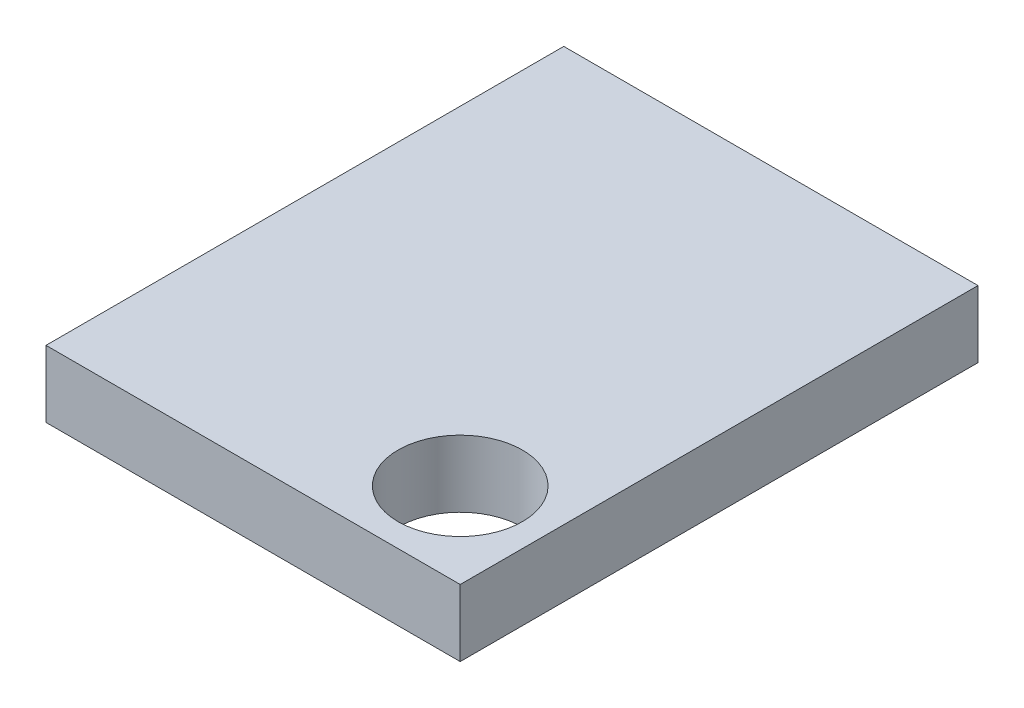
SolidWorks part; units mm, degrees
ref_plane "Front Plane" through (0, 0, 0) normal (0, 0, 1) x (1, 0, 0)
ref_plane "Top Plane" through (0, 0, 0) normal (0, 1, 0) x (1, 0, 0)
ref_plane "Right Plane" through (0, 0, 0) normal (1, 0, 0) x (0, 0, -1)
sketch "Sketch1" plane through (0, 0, 0) normal (0, 1, 0) x (1, 0, 0)
  line L1 (-5.08, -6.35) -> (5.08, -6.35)
  line L2 (-5.08, -6.35) -> (-5.08, 6.35)
  line L3 (-5.08, 6.35) -> (5.08, 6.35)
  line L4 (5.08, -6.35) -> (5.08, 6.35)
  line L5 (-5.08, -6.35) -> (5.08, 6.35) construction
  line L6 (-5.08, 6.35) -> (5.08, -6.35) construction
  point P0 (0, 0)
  dimension "D1" = 12.7
  dimension "D2" = 10.16
extrude "Boss-Extrude1" add sketch "Sketch1" along normal blind 1.6383
sketch "Sketch2" plane through (0, 1.6383, 0) normal (0, 1, 0) x (1, 0, 0)
  line L0 (0, 0) -> (29.1011, 0) construction
  line L1 (5.08, -6.35) -> (5.08, 6.35) construction
  line L2 (-5.08, -6.35) -> (5.08, -6.35) construction
  circle A0 centre (2.9845, -4.2545) radius 1.524
  dimension "D1" = 3.048
  dimension "D3" = 2.0955
  dimension "D2" = 2.0955
extrude "Cut-Extrude1" cut sketch "Sketch2" against normal blind 1.6383
ref_plane "Plane1" through (0, 0, 0) normal (0, 0, -1) x (-1, 0, 0)
